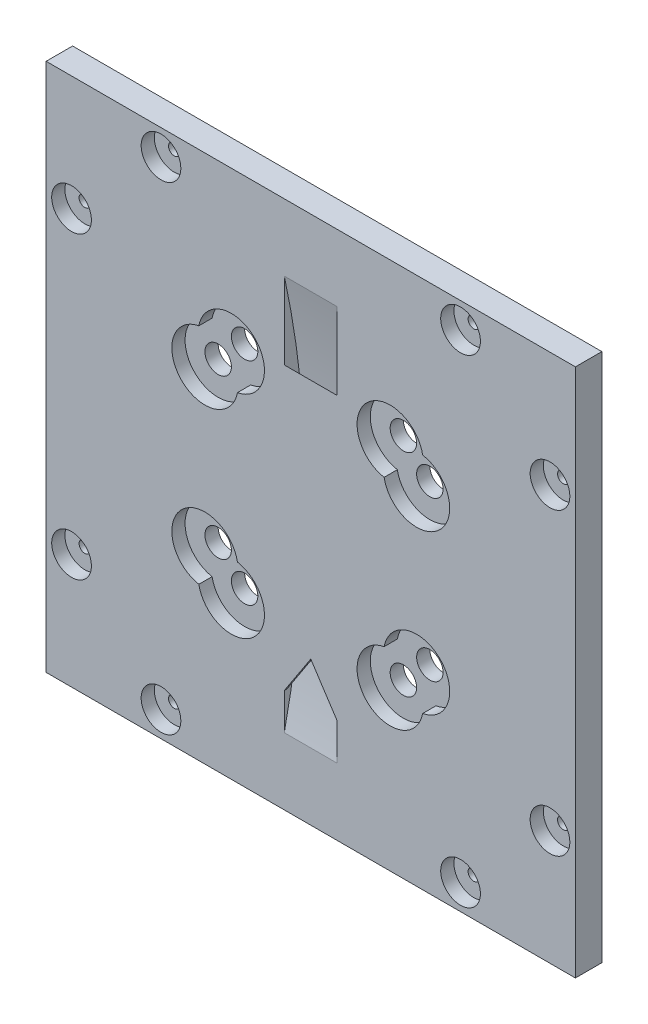
SolidWorks part; units mm, degrees
ref_plane "Front Plane" through (0, 0, 0) normal (0, 0, 1) x (1, 0, 0)
ref_plane "Top Plane" through (0, 0, 0) normal (0, 1, 0) x (1, 0, 0)
ref_plane "Right Plane" through (0, 0, 0) normal (1, 0, 0) x (0, 0, -1)
sketch "Sketch1" plane through (0, 0, 0) normal (0, 0, 1) x (1, 0, 0)
  line L1 (-100, 100) -> (100, 100)
  line L2 (-100, 100) -> (-100, -100)
  line L3 (-100, -100) -> (100, -100)
  line L4 (100, 100) -> (100, -100)
  line L5 (-100, 100) -> (100, -100) construction
  line L6 (-100, -100) -> (100, 100) construction
  point P0 (0, 0)
  dimension "D1" = 200
  dimension "D2" = 200
extrude "Boss-Extrude1" add sketch "Sketch1" along normal blind 10
sketch "Sketch2" plane through (0, 0, 10) normal (0, 0, 1) x (1, 0, 0)
  line L1 (-40, 30) -> (40, 30) construction
  line L2 (-40, 30) -> (-40, -30) construction
  line L3 (-40, -30) -> (40, -30) construction
  line L4 (40, 30) -> (40, -30) construction
  line L5 (-40, 30) -> (40, -30) construction
  line L6 (-40, -30) -> (40, 30) construction
  line L7 (30, 40) -> (-30, 40) construction
  line L8 (30, 40) -> (30, -40) construction
  line L9 (30, -40) -> (-30, -40) construction
  line L10 (-30, 40) -> (-30, -40) construction
  line L11 (30, 40) -> (-30, -40) construction
  line L12 (30, -40) -> (-30, 40) construction
  line L13 (-90.4, 56.6) -> (90.4, 56.6) construction
  line L14 (-90.4, 56.6) -> (-90.4, -56.6) construction
  line L15 (-90.4, -56.6) -> (90.4, -56.6) construction
  line L16 (90.4, 56.6) -> (90.4, -56.6) construction
  line L17 (-90.4, 56.6) -> (90.4, -56.6) construction
  line L18 (-90.4, -56.6) -> (90.4, 56.6) construction
  line L19 (-56.6, 90.4) -> (56.6, 90.4) construction
  line L20 (-56.6, 90.4) -> (-56.6, -90.4) construction
  line L21 (-56.6, -90.4) -> (56.6, -90.4) construction
  line L22 (56.6, 90.4) -> (56.6, -90.4) construction
  line L23 (-56.6, 90.4) -> (56.6, -90.4) construction
  line L24 (-56.6, -90.4) -> (56.6, 90.4) construction
  circle A0 centre (-40, 30) radius 5
  circle A1 centre (40, 30) radius 5
  circle A2 centre (40, -30) radius 5
  circle A3 centre (-40, -30) radius 5
  circle A4 centre (-30, 40) radius 5
  circle A5 centre (30, 40) radius 5
  circle A6 centre (30, -40) radius 5
  circle A7 centre (-30, -40) radius 5
  circle A8 centre (-56.6, 90.4) radius 2.15
  circle A9 centre (-90.4, 56.6) radius 2.15
  circle A10 centre (-90.4, -56.6) radius 2.15
  circle A11 centre (-56.6, -90.4) radius 2.15
  circle A12 centre (56.6, -90.4) radius 2.15
  circle A13 centre (90.4, -56.6) radius 2.15
  circle A14 centre (90.4, 56.6) radius 2.15
  circle A15 centre (56.6, 90.4) radius 2.15
  point P0 (0, 0)
  point P10 (0, 0)
  point P19 (0, 0)
  point P24 (0, 0)
  dimension "D3" = 10
  dimension "D4" = 113.2
  dimension "D6" = 4.3
  dimension "D1" = 60
  dimension "D2" = 80
  dimension "D5" = 180.8
extrude "Cut-Extrude1" cut sketch "Sketch2" against normal through all
sketch "Sketch3" plane through (0, 0, 0) normal (0, 1, 0) x (1, 0, 0)
  line L0 (0, -4.4923) -> (0, -354.4923) construction
  line L1 (-10, -6.9923) -> (10, -6.9923)
  line L2 (-10, -6.9923) -> (-10, -1.9923)
  line L3 (-10, -1.9923) -> (10, -1.9923)
  line L4 (10, -6.9923) -> (10, -1.9923)
  line L5 (-10, -6.9923) -> (10, -1.9923) construction
  line L6 (-10, -1.9923) -> (10, -6.9923) construction
  line L7 (0, -354.4923) -> (23.0759, -354.4923) construction
  point P0 (0, -4.4923)
  dimension "D1" = 350
  dimension "D2" = 20
  dimension "D3" = 5
revolve "Cut-Revolve1" cut sketch "Sketch3" angle 360 about L7
sketch "Sketch4" plane through (0, 0, 10) normal (0, 0, 1) x (1, 0, 0)
  circle A0 centre (40, -30) radius 12.5
  circle A1 centre (30, -40) radius 12.5
  circle A2 centre (-30, -40) radius 12.5
  circle A3 centre (-40, -30) radius 12.5
  circle A4 centre (-40, 30) radius 12.5
  circle A5 centre (-30, 40) radius 12.5
  circle A6 centre (30, 40) radius 12.5
  circle A7 centre (40, 30) radius 12.5
  circle A8 centre (90.4, 56.6) radius 7.5
  circle A9 centre (56.6, 90.4) radius 7.5
  circle A10 centre (-56.6, 90.4) radius 7.5
  circle A11 centre (-90.4, 56.6) radius 7.5
  circle A12 centre (-90.4, -56.6) radius 7.5
  circle A13 centre (-56.6, -90.4) radius 7.5
  circle A14 centre (56.6, -90.4) radius 7.5
  circle A15 centre (90.4, -56.6) radius 7.5
  circle M7 centre (-56.6, 90.4) radius 2.15
  circle M8 centre (-30, -40) radius 5
  circle M9 centre (30, -40) radius 5
  circle M10 centre (30, 40) radius 5
  circle M11 centre (-30, 40) radius 5
  circle M12 centre (-40, -30) radius 5
  circle M13 centre (40, -30) radius 5
  circle M14 centre (40, 30) radius 5
  circle M15 centre (56.6, 90.4) radius 2.15
  circle M16 centre (90.4, 56.6) radius 2.15
  circle M17 centre (90.4, -56.6) radius 2.15
  circle M18 centre (56.6, -90.4) radius 2.15
  circle M21 centre (-90.4, 56.6) radius 2.15
  circle M22 centre (-40, 30) radius 5
  dimension "D1" = 25
  dimension "D2" = 15
extrude "Cut-Extrude2" cut sketch "Sketch4" against normal blind 5 contours A7 A6 M10 | A6 A7 M10 M14 | A6 A7 M14 | A1 A0 M13 | A1 A0 M13 M9 | A0 A1 M9 | A2 A3 M12 | A2 A3 M8 M12 | A4 A5 M11 | A4 A5 M22 M11 | A5 A4 M22 | A10 M7 | A11 M21 | A14 M18 | A15 M17 | A8 M16 | A9 M15 | A12 | A13
sketch "Sketch6" plane through (0, 0, 10) normal (0, 0, 1) x (1, 0, 0)
  line L0 (0, -45.6216) -> (10, -60.912)
  line L1 (-10, -45.6216) -> (-10, -37.9976)
  line L2 (10, -60.912) -> (10, -45.6216)
  line L3 (10, -45.6216) -> (0, -45.6216)
  line L4 (0, -45.6216) -> (-10, -45.6216)
  line L5 (-10, -45.6216) -> (-10, -60.912)
  line L6 (-10, -74.7083) -> (-10, -45.6216) construction
  line L7 (-10, -60.912) -> (0, -45.6216)
  line L8 (-10, -37.9976) -> (10, -37.9976)
  line L9 (10, -37.9976) -> (10, -45.6216)
extrude "Boss-Extrude3" add sketch "Sketch6" against normal blind 1
